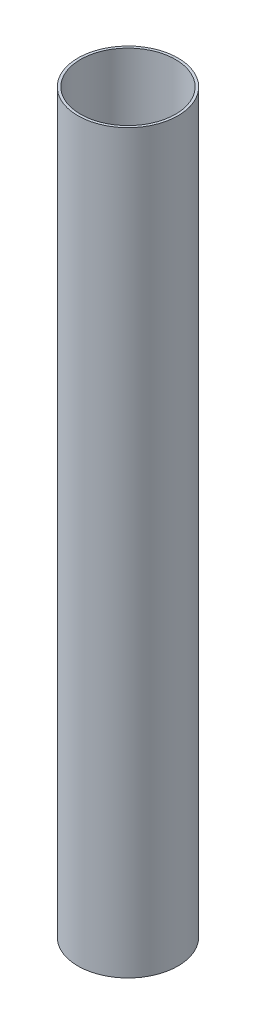
SolidWorks part; units mm, degrees
ref_plane "Front Plane" through (0, 0, 0) normal (0, 0, 1) x (1, 0, 0)
ref_plane "Top Plane" through (0, 0, 0) normal (0, 1, 0) x (1, 0, 0)
ref_plane "Right Plane" through (0, 0, 0) normal (1, 0, 0) x (0, 0, -1)
sketch "Sketch1" plane through (0, 0, 0) normal (0, 1, 0) x (1, 0, 0)
  circle A0 centre (0, 0) radius 32.258
  circle A1 centre (0, 0) radius 33.9725
  dimension "D1" = 64.516
  dimension "D2" = 67.945
extrude "Boss-Extrude1" add sketch "Sketch1" along normal blind 500
